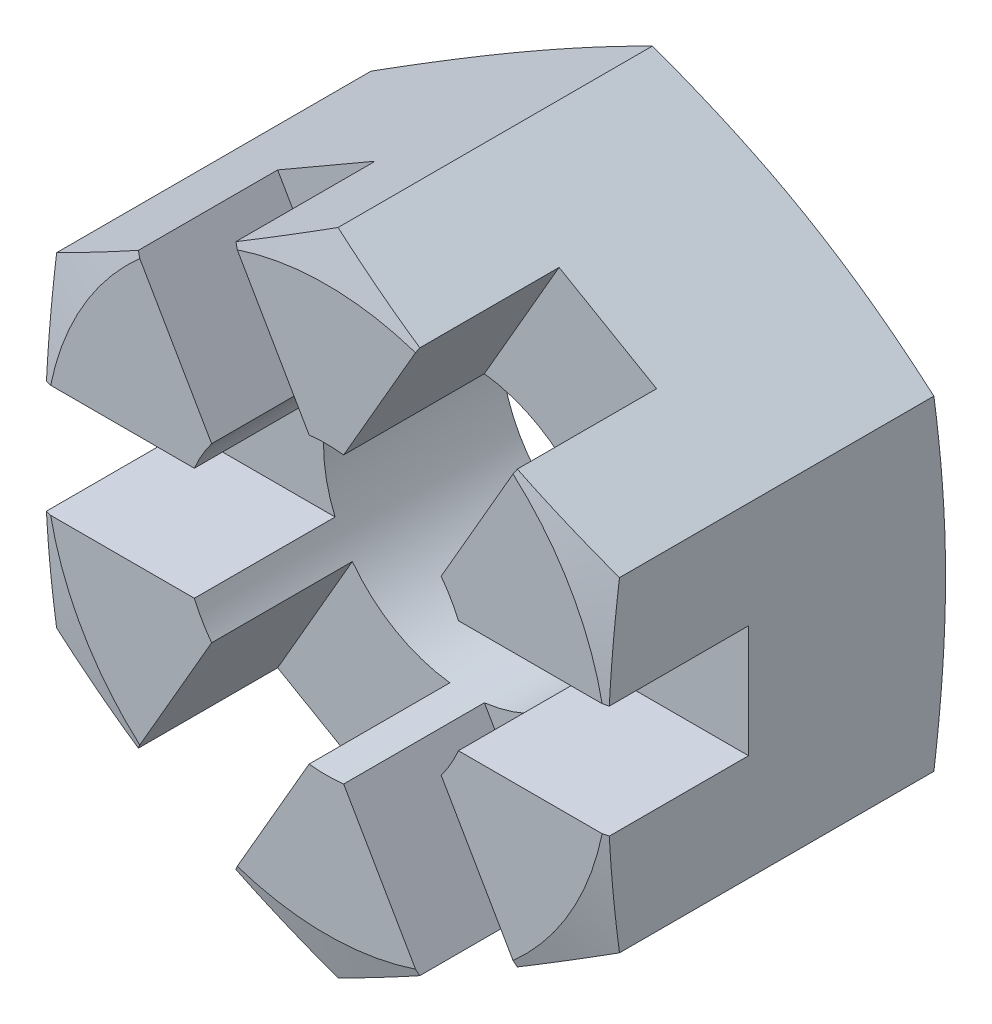
SolidWorks part; units mm, degrees
ref_plane "Přední rovina" through (0, 0, 0) normal (0, 0, 1) x (1, 0, 0)
ref_plane "Vrchní rovina" through (0, 0, 0) normal (0, 1, 0) x (1, 0, 0)
ref_plane "Pravá rovina" through (0, 0, 0) normal (1, 0, 0) x (0, 0, -1)
sketch "Skica1" plane through (0, 0, 0) normal (0, 0, 1) x (1, 0, 0)
  line L1 (5, -2.8868) -> (5, 2.8868)
  line L2 (5, 2.8868) -> (0, 5.7735)
  line L3 (0, 5.7735) -> (-5, 2.8868)
  line L4 (-5, 2.8868) -> (-5, -2.8868)
  line L5 (-5, -2.8868) -> (0, -5.7735)
  line L6 (0, -5.7735) -> (5, -2.8868)
  circle A0 centre (0, 0) radius 5 construction
  dimension "s" = 10
extrude "Vysunout1" add sketch "Skica1" along normal blind 6
sketch "Skica3" plane through (0, 0, 0) normal (0, 1, 0) x (1, 0, 0)
  line L0 (-5, 0) -> (-16.1962, 0)
  line L1 (-16.1962, 0) -> (-16.1962, -6)
  line L2 (-16.1962, -6) -> (-5, -6)
  line L3 (-5, 0) -> (-16.1962, -3)
  line L4 (-16.1962, -3) -> (-5, -6)
  line L5 (0, 0) -> (0, -6) construction
  dimension "D1" = 15
revolve "Odebrat otočením1" cut sketch "Skica3" angle 360 about L5
sketch "Skica4" plane through (0, 0, 0) normal (0, 0, -1) x (-1, 0, 0)
  circle A0 centre (0, 0) radius 2.55
  dimension "D1" = 5.1
extrude "Odebrat vysunutím1" cut sketch "Skica4" against normal through all
cosmetic thread "Kosmetický závit1" parameters "M"=6
sketch "Skica5" plane through (0, 0, 6) normal (0, 0, 1) x (1, 0, 0)
  line L0 (0, 0) -> (5, 0) construction
  line L1 (-5, 1) -> (5, 1)
  line L2 (-5, 1) -> (-5, -1)
  line L3 (-5, -1) -> (5, -1)
  line L4 (5, 1) -> (5, -1)
  line L5 (5, 0) -> (5, 2.8868) construction
  line L6 (-5, 2.8868) -> (-5, 0) construction
  dimension "n" = 2
extrude "Odebrat vysunutím2" cut sketch "Skica5" against normal blind 2.5
pattern_circular "Kruhové pole1" count 3 over 360 about axis through (0, 0, 0) along (0, 0, 1) of "Odebrat vysunutím2"
chamfer "Zkosit1" distance 0.6 angle 30 1 edges at (-2.55, 0, 0)
equation "\"D1@Skica4\" = \"M@Kosmetický závit1\"*0.85"
